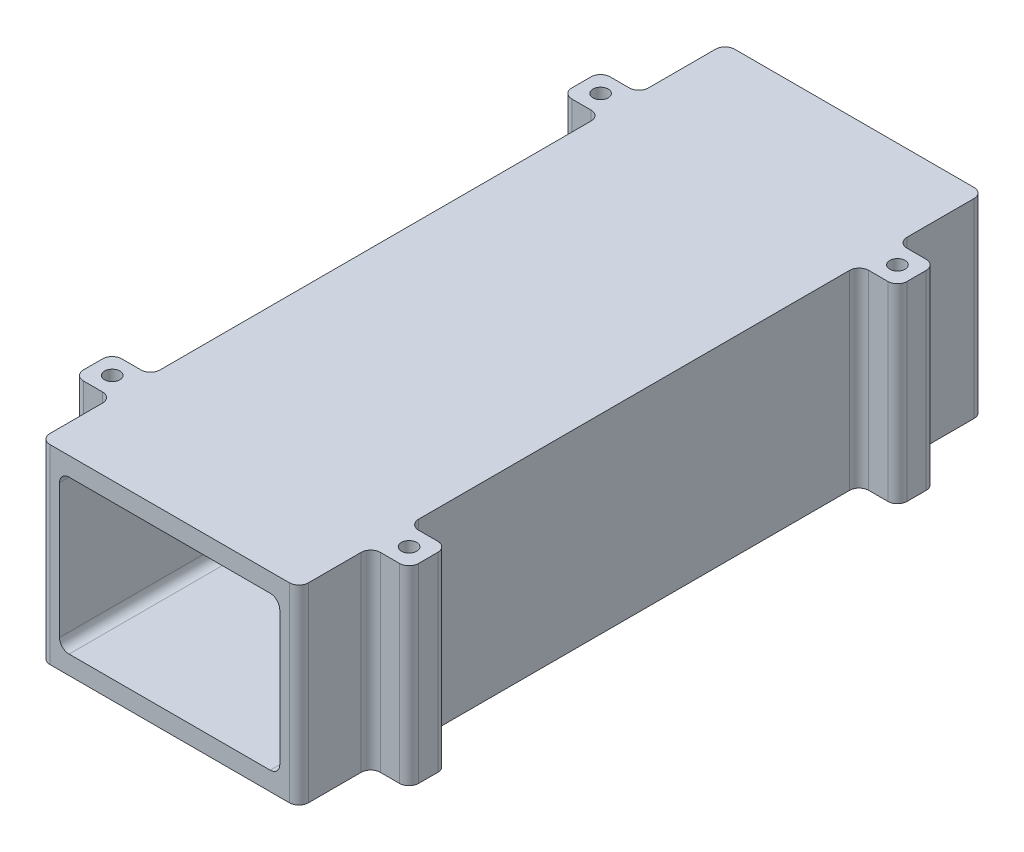
SolidWorks part; units mm, degrees
ref_plane "前视基准面" through (0, 0, 0) normal (0, 0, 1) x (1, 0, 0)
ref_plane "上视基准面" through (0, 0, 0) normal (0, 1, 0) x (1, 0, 0)
ref_plane "右视基准面" through (0, 0, 0) normal (1, 0, 0) x (0, 0, -1)
sketch "草图1" plane through (0, 0, 0) normal (0, 0, 1) x (1, 0, 0)
  line L1 (-23, 16) -> (23, 16)
  line L2 (-23, 16) -> (-23, -16)
  line L3 (-23, -16) -> (23, -16)
  line L4 (23, 16) -> (23, -16)
  line L5 (-23, 16) -> (23, -16) construction
  line L6 (-23, -16) -> (23, 16) construction
  line L7 (-27, 19.9) -> (27, 19.9)
  line L8 (-27, 19.9) -> (-27, -19.9)
  line L9 (-27, -19.9) -> (27, -19.9)
  line L10 (27, 19.9) -> (27, -19.9)
  line L11 (-27, 19.9) -> (27, -19.9) construction
  line L12 (-27, -19.9) -> (27, 19.9) construction
  point P0 (0, 0)
  point P5 (0, 0)
  dimension "D1" = 32
  dimension "D2" = 46
  dimension "D3" = 39.8
  dimension "D4" = 54
extrude "凸台-拉伸1" add sketch "草图1" along normal blind 143
sketch "草图3" plane through (0, 0, 0) normal (0, 0, -1) x (-1, 0, 0)
  line L1 (-27, 19.9) -> (27, 19.9)
  line L2 (-27, 19.9) -> (-27, -19.9)
  line L3 (-27, -19.9) -> (27, -19.9)
  line L4 (27, 19.9) -> (27, -19.9)
extrude "凸台-拉伸2" add sketch "草图3" along normal blind 3
sketch "草图4" plane through (0, 19.9, 0) normal (0, 1, 0) x (1, 0, 0)
  line L0 (0, 3) -> (0, -143) construction
  line L1 (-27, 3) -> (27, 3) construction
  line L2 (27, -143) -> (-27, -143) construction
  line L3 (-27, -70) -> (27, -70) construction
  line L4 (-27, -143) -> (-27, 3) construction
  line L5 (27, -143) -> (27, 3) construction
  line L6 (-27, -117) -> (-35, -117)
  line L7 (27, -125) -> (35, -125)
  line L8 (27, -125) -> (27, -117)
  line L9 (27, -117) -> (35, -117)
  line L10 (35, -125) -> (35, -117)
  line L11 (-35, -125) -> (-35, -117)
  line L12 (-27, -125) -> (-35, -125)
  line L13 (-27, -125) -> (-27, -117)
  line L14 (27, -23) -> (35, -23)
  line L15 (35, -15) -> (35, -23)
  line L16 (27, -15) -> (35, -15)
  line L17 (27, -15) -> (27, -23)
  line L18 (-27, -15) -> (-27, -23)
  line L19 (-27, -15) -> (-35, -15)
  line L20 (-35, -15) -> (-35, -23)
  line L21 (-27, -23) -> (-35, -23)
  line L22 (27, -121) -> (35, -121) construction
  line L23 (31, -117) -> (31, -125) construction
  circle A1 centre (31, -121) radius 1.6
  circle A2 centre (-31, -121) radius 1.6
  circle A3 centre (31, -19) radius 1.6
  circle A4 centre (-31, -19) radius 1.6
  dimension "D1" = 18
  dimension "D4" = 3.2
  dimension "D2" = 8
  dimension "D3" = 8
extrude "凸台-拉伸3" add sketch "草图4" against normal blind 39.8
fillet "圆角2" radius 2 4 edges at (-23, -16, 71.5) (23, -16, 71.5) (23, 16, 71.5) (-23, 16, 71.5)
sketch "草图5" plane through (0, 0, 143) normal (0, 0, 1) x (1, 0, 0)
  line L1 (-27, -19.9) -> (27, -19.9)
  line L2 (-27, -19.9) -> (-27, 19.9)
  line L3 (-27, 19.9) -> (27, 19.9)
  line L4 (27, -19.9) -> (27, 19.9)
extrude "切除-拉伸1" cut sketch "草图5" against normal blind 3
fillet "圆角3" radius 2 20 edges at (-27, 0, 140) (27, 0, 140) (27, 0, -3) (-27, 0, -3) (27, 0, 125) (27, 0, 117) (35, 0, 117) (35, 0, 125) (-27, 0, 117) (-27, 0, 125) (-35, 0, 125) (-35, 0, 117) (27, 0, 23) (27, 0, 15) (35, 0, 15) (35, 0, 23) (-35, 0, 15) (-27, 0, 15) (-27, 0, 23) (-35, 0, 23)
